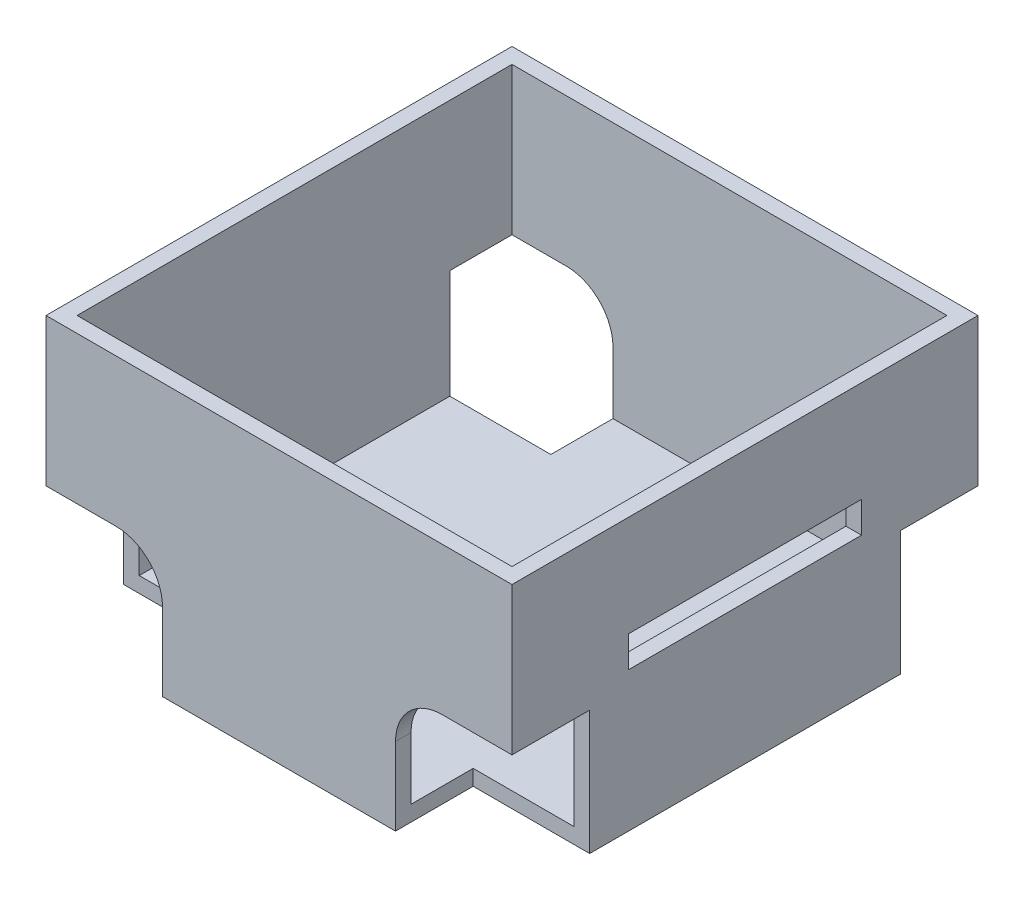
SolidWorks part; units mm, degrees
material "1060 Alloy"
ref_plane "Front Plane" through (0, 0, 0) normal (0, 0, 1) x (1, 0, 0)
ref_plane "Top Plane" through (0, 0, 0) normal (0, 1, 0) x (1, 0, 0)
ref_plane "Right Plane" through (0, 0, 0) normal (1, 0, 0) x (0, 0, -1)
sketch "Sketch1" plane through (0, 0, 0) normal (0, 1, 0) x (1, 0, 0)
  line L1 (-150, -150) -> (150, -150)
  line L2 (-150, -150) -> (-150, 150)
  line L3 (-150, 150) -> (150, 150)
  line L4 (150, -150) -> (150, 150)
  line L5 (-150, -150) -> (150, 150) construction
  line L6 (-150, 150) -> (150, -150) construction
  point P0 (0, 0)
  dimension "D2" = 300
extrude "Boss-Extrude1" add sketch "Sketch1" along normal blind 175
shell "Shell1" thickness 10
sketch "Sketch4" plane through (0, 0, 150) normal (0, 0, 1) x (1, 0, 0)
  line L0 (0, 0) -> (75, 0)
  line L1 (-150, 0) -> (150, 0) construction
  line L2 (75, 0) -> (75, 50)
  line L3 (105, 80) -> (150, 80)
  line L4 (150, 175) -> (150, 0) construction
  line L5 (0, 0) -> (-75, 0)
  line L6 (-75, 0) -> (-75, 50)
  line L7 (-105, 80) -> (-150, 80)
  line L8 (-150, 175) -> (-150, 0) construction
  line L9 (-150, 80) -> (-150, -5)
  line L10 (-150, -5) -> (150, -5)
  line L11 (150, -5) -> (150, 80)
  arc A0 (75, 50) -> (105, 80) centre (105, 50) cw
  arc A1 (-75, 50) -> (-105, 80) centre (-105, 50) ccw
  dimension "D6" = 30
  dimension "D1" = 80
  dimension "D2" = 80
  dimension "D3" = 75
  dimension "D4" = 75
  dimension "D5" = 5
extrude "Cut-Extrude5" cut sketch "Sketch4" against normal blind 50
sketch "Sketch7" plane through (0, 0, -150) normal (0, 0, -1) x (-1, 0, 0)
  line L0 (0, 0) -> (75, 0)
  line L1 (75, 0) -> (75, 50)
  line L2 (105, 80) -> (150, 80)
  line L3 (0, 0) -> (-75, 0)
  line L4 (-75, 0) -> (-75, 50)
  line L5 (-105, 80) -> (-150, 80)
  line L6 (-150, 80) -> (-150, -5)
  line L7 (-150, -5) -> (150, -5)
  line L8 (150, -5) -> (150, 80)
  line L9 (150, 175) -> (150, 0) construction
  line L10 (-150, 0) -> (150, 0) construction
  line L11 (-150, 175) -> (-150, 0) construction
  arc A0 (75, 50) -> (105, 80) centre (105, 50) cw
  arc A1 (-75, 50) -> (-105, 80) centre (-105, 50) ccw
  dimension "D4" = 30
  dimension "D1" = 75
  dimension "D2" = 75
  dimension "D3" = 5
  dimension "D5" = 80
  dimension "D6" = 80
extrude "Cut-Extrude6" cut sketch "Sketch7" against normal blind 50
sketch "Sketch8" plane through (150, 0, 0) normal (1, 0, 0) x (0, 0, -1)
  line L0 (0, 100) -> (0, 0) construction
  line L1 (75, 90) -> (-75, 90)
  line L2 (75, 90) -> (75, 110)
  line L3 (75, 110) -> (-75, 110)
  line L4 (-75, 90) -> (-75, 110)
  line L5 (75, 90) -> (-75, 110) construction
  line L6 (75, 110) -> (-75, 90) construction
  line L7 (0, 0) -> (0, 100)
  point P0 (0, 100)
  dimension "D1" = 150
  dimension "D2" = 100
  dimension "D3" = 20
extrude "Cut-Extrude7" cut sketch "Sketch8" against normal up to next and the other way through all
